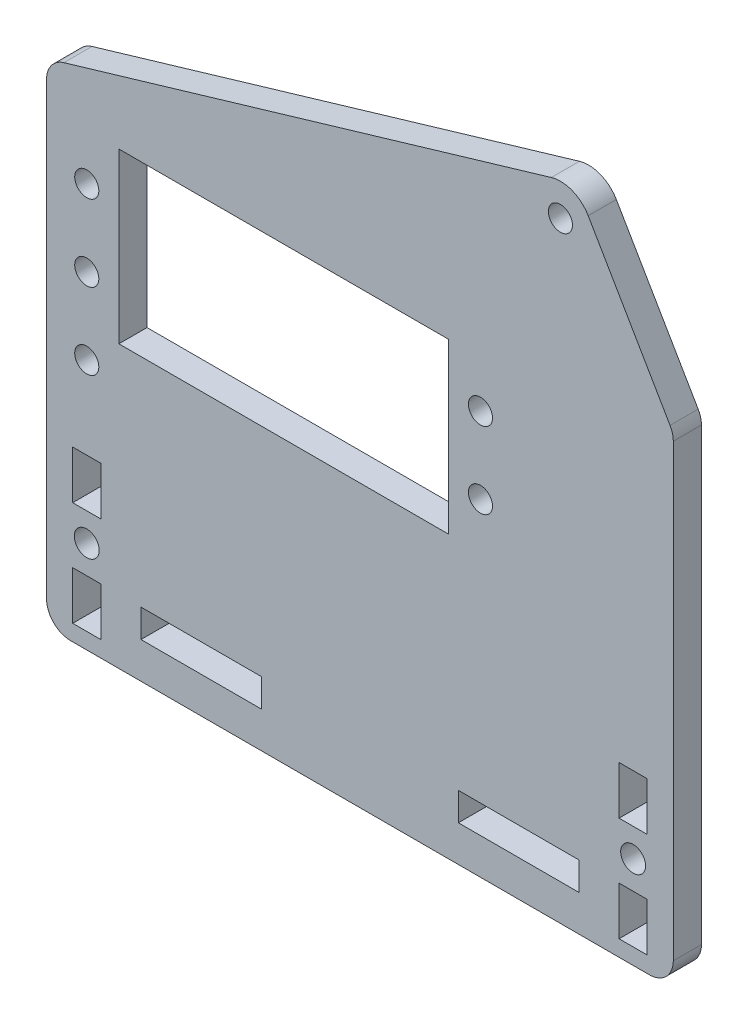
SolidWorks part; units mm, degrees
material "Balsa"
ref_plane "Front Plane" through (0, 0, 0) normal (0, 0, 1) x (1, 0, 0)
ref_plane "Top Plane" through (0, 0, 0) normal (0, 1, 0) x (1, 0, 0)
ref_plane "Right Plane" through (0, 0, 0) normal (1, 0, 0) x (0, 0, -1)
sketch "Sketch1" plane through (0, 0, 0) normal (0, 0, 1) x (1, 0, 0)
  line L0 (26.0811, 45) -> (23.8224, 45) construction
  line L1 (-36, -31) -> (36, -31)
  line L2 (-39, -28) -> (-39, 28)
  line L3 (-36.4347, 31) -> (36.4347, 31) construction
  line L4 (39, -28) -> (39, 28)
  line L5 (0, 31) -> (0, -31) construction
  line L6 (-39, 0) -> (39, 0) construction
  line L7 (-30, 4) -> (11, 4)
  line L8 (-30, 4) -> (-30, 25)
  line L9 (-30, 25) -> (11, 25)
  line L10 (11, 4) -> (11, 25)
  line L11 (24.9518, 54.2026) -> (24.9518, 47.4582) construction
  line L12 (23.8164, 48.8355) -> (-36.8515, 30.8766)
  line L13 (28.4091, 47.0116) -> (38.593, 29.5087)
  line L14 (11, 14.5) -> (-30, 14.5) construction
  line L15 (-19.61, 18.0838) -> (-19.61, 10.9162) construction
  arc A0 (38.593, 29.5087) -> (39, 28) centre (36, 28) cw
  arc A1 (36, -31) -> (39, -28) centre (36, -28) ccw
  arc A2 (-36, -31) -> (-39, -28) centre (-36, -28) cw
  arc A3 (-39, 28) -> (-36.8515, 30.8766) centre (-36, 28) cw
  circle A4 centre (24.9518, 45) radius 1.5
  arc A5 (23.8164, 48.8355) -> (28.4091, 47.0116) centre (24.9518, 45) cw
  point P0 (0, 0)
  point P8 (39, -31)
  point P12 (-39, -31)
  point P33 (-19.61, 14.5)
  dimension "D2" = 3
  dimension "D3" = 62
  dimension "D10" = 3
  dimension "D11" = 4
  dimension "D1" = 28
  dimension "D4" = 41
  dimension "D5" = 21
  dimension "D6" = 9
  dimension "D7" = 6
  dimension "D8" = 54
  dimension "D9" = 20
  dimension "D12" = 10.39
extrude "Boss-Extrude1" add sketch "Sketch1" along normal blind 3.5
sketch "Sketch2" plane through (0, 0, 0) normal (0, 0, -1) x (-1, 0, 0)
  line L0 (-39, -19.5) -> (39, -19.5) construction
  line L1 (-39, -28) -> (-39, 28) construction
  line L2 (39, 28) -> (39, -28) construction
  line L3 (36, -31) -> (-36, -31) construction
  line L4 (-34, -8) -> (-34, -31) construction
  line L5 (0, 9.9619) -> (0, -7.9273) construction
  line L6 (-35.75, -16) -> (-32.25, -16)
  line L7 (-35.75, -16) -> (-35.75, -10)
  line L8 (-35.75, -10) -> (-32.25, -10)
  line L9 (-32.25, -16) -> (-32.25, -10)
  line L10 (-34, -10) -> (-34, -16) construction
  line L11 (-35.75, -13) -> (-32.25, -13) construction
  line L12 (-35.75, -29) -> (-32.25, -29)
  line L13 (-35.75, -29) -> (-35.75, -23)
  line L14 (-35.75, -23) -> (-32.25, -23)
  line L15 (-32.25, -29) -> (-32.25, -23)
  line L16 (-34, -23) -> (-34, -29) construction
  line L17 (-35.75, -26) -> (-32.25, -26) construction
  line L18 (35.75, -29) -> (32.25, -29)
  line L19 (35.75, -29) -> (35.75, -23)
  line L20 (35.75, -23) -> (32.25, -23)
  line L21 (32.25, -29) -> (32.25, -23)
  line L22 (35.75, -16) -> (32.25, -16)
  line L23 (35.75, -16) -> (35.75, -10)
  line L24 (35.75, -10) -> (32.25, -10)
  line L25 (32.25, -16) -> (32.25, -10)
  circle A0 centre (-34, -19.5) radius 1.55
  circle A1 centre (34, -19.5) radius 1.55
  point P10 (-34, -13)
  point P14 (-34, -26)
  dimension "D8" = 3.1
  dimension "D1" = 11.5
  dimension "D2" = 5
  dimension "D3" = 3.5
  dimension "D4" = 6
  dimension "D5" = 6
  dimension "D6" = 19
  dimension "D9" = 0
extrude "Cut-Extrude1" cut sketch "Sketch2" against normal through all
sketch "Sketch3" plane through (0, 0, 0) normal (0, 0, -1) x (-1, 0, 0)
  line L0 (-32.25, -23) -> (32.25, -23) construction
  line L1 (0, 0) -> (0, -31.4864) construction
  line L2 (27.25, -23) -> (27.25, -26.5)
  line L3 (-27.25, -23) -> (-12.25, -23)
  line L4 (-27.25, -23) -> (-27.25, -26.5)
  line L5 (-27.25, -26.5) -> (-12.25, -26.5)
  line L6 (-12.25, -23) -> (-12.25, -26.5)
  line L7 (27.25, -23) -> (12.25, -23)
  line L8 (12.25, -23) -> (12.25, -26.5)
  line L9 (27.25, -26.5) -> (12.25, -26.5)
  dimension "D1" = 24.5
  dimension "D2" = 15
  dimension "D3" = 3.5
extrude "Cut-Extrude2" cut sketch "Sketch3" against normal through all
sketch "Sketch4" plane through (0, 0, 0) normal (0, 0, -1) x (-1, 0, 0)
  line L0 (-15, 14.5) -> (30, 14.5) construction
  line L1 (9.5, 28.7883) -> (9.5, -1.2827) construction
  line L2 (-11, 25) -> (30, 25) construction
  line L3 (30, 4) -> (-11, 4) construction
  line L4 (30, 25) -> (30, 4) construction
  line L5 (-11, 4) -> (-11, 25) construction
  line L7 (-15, 9.75) -> (34, 9.75) construction
  line L8 (-15, 9.75) -> (-15, 19.25) construction
  line L9 (-15, 19.25) -> (34, 19.25) construction
  line L10 (34, 9.75) -> (34, 19.25) construction
  line L11 (9.5, 19.25) -> (9.5, 9.75) construction
  line L12 (-15, 14.5) -> (34, 14.5) construction
  circle A0 centre (-15, 19.25) radius 1.5
  circle A1 centre (-15, 9.75) radius 1.5
  circle A2 centre (34, 9.75) radius 1.5
  circle A3 centre (34, 19.25) radius 1.5
  point P12 (9.5, 14.5)
  dimension "D3" = 3
  dimension "D1" = 9.5
  dimension "D2" = 49
extrude "Cut-Extrude3" cut sketch "Sketch4" against normal through all
sketch "Sketch5" plane through (0, 0, 0) normal (0, 0, -1) x (-1, 0, 0)
  line L0 (34, -31) -> (34, 31.7207) construction
  line L3 (36, -31) -> (-36, -31) construction
  line L4 (-23.8164, 48.8355) -> (36.8515, 30.8766) construction
  circle A0 centre (34, 0.25) radius 1.5
  circle A8 centre (34, 19.25) radius 1.5 construction
  circle A10 centre (34, 19.25) radius 1.5
  circle A11 centre (34, 9.75) radius 1.5 construction
  circle A12 centre (34, 9.75) radius 1.5
  dimension "D1" = 2
extrude "Cut-Extrude5" cut sketch "Sketch5" against normal up to next contours A0
